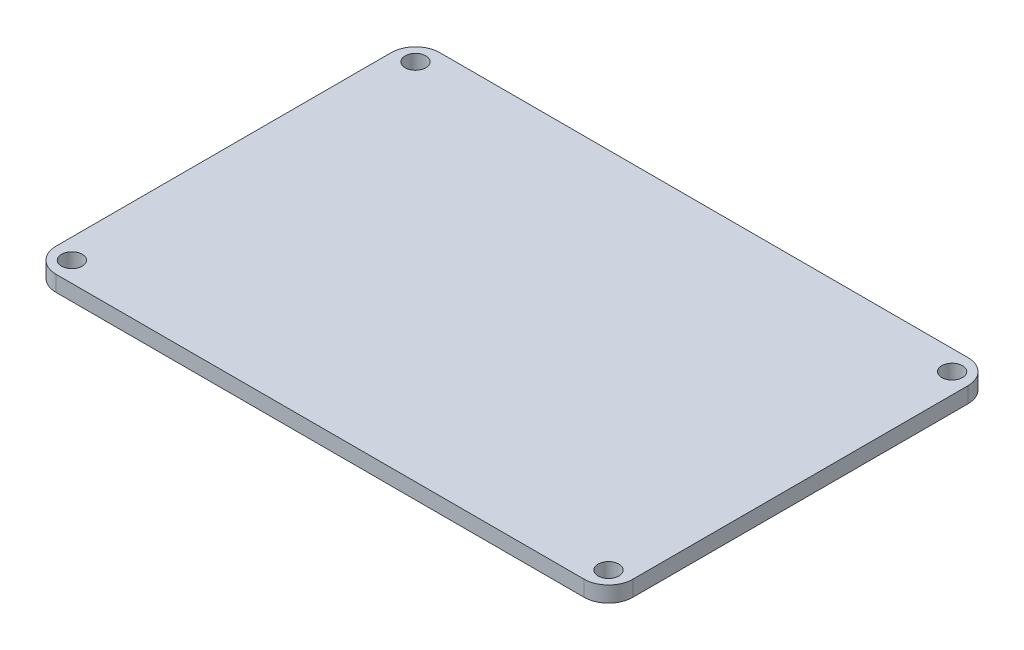
SolidWorks part; units mm, degrees
ref_plane "Front Plane" through (0, 0, 0) normal (0, 0, 1) x (1, 0, 0)
ref_plane "Top Plane" through (0, 0, 0) normal (0, 1, 0) x (1, 0, 0)
ref_plane "Right Plane" through (0, 0, 0) normal (1, 0, 0) x (0, 0, -1)
sketch "Sketch1" plane through (0, 0, 0) normal (0, 1, 0) x (1, 0, 0)
  line L1 (0, 0) -> (60.1218, 0)
  line L2 (0, 0) -> (0, 40.005)
  line L3 (0, 40.005) -> (60.1218, 40.005)
  line L4 (60.1218, 0) -> (60.1218, 40.005)
  dimension "D1" = 60.1218
  dimension "D2" = 40.005
extrude "Boss-Extrude1" add sketch "Sketch1" along normal blind 1.6383
fillet "Fillet1" radius 2.54 4 edges at (0, 0.8192, -40.005) (60.1218, 0.8192, -40.005) (60.1218, 0.8192, 0) (0, 0.8192, 0)
sketch "Sketch3" plane through (0, 1.6383, 0) normal (0, 1, 0) x (1, 0, 0)
  line L0 (0, 37.465) -> (0, 2.54) construction
  line L1 (2.54, 0) -> (57.5818, 0) construction
  circle A0 centre (2.0955, 2.0955) radius 1.0795
  dimension "D1" = 2.0955
  dimension "D2" = 2.0955
  dimension "D3" = 2.159
extrude "Cut-Extrude2" cut sketch "Sketch3" against normal through all
ref_plane "Plane3" through (30.0609, 0, 0) normal (1, 0, 0) x (0, 0, -1)
ref_plane "Plane4" through (0, 0, -20.0025) normal (0, 0, 1) x (1, 0, 0)
mirror "Mirror1" about plane through (0, 0, -20.0025) normal (0, 0, 1) of "Cut-Extrude2"
mirror "Mirror2" about plane through (30.0609, 0, 0) normal (1, 0, 0) of "Mirror1", "Cut-Extrude2"
